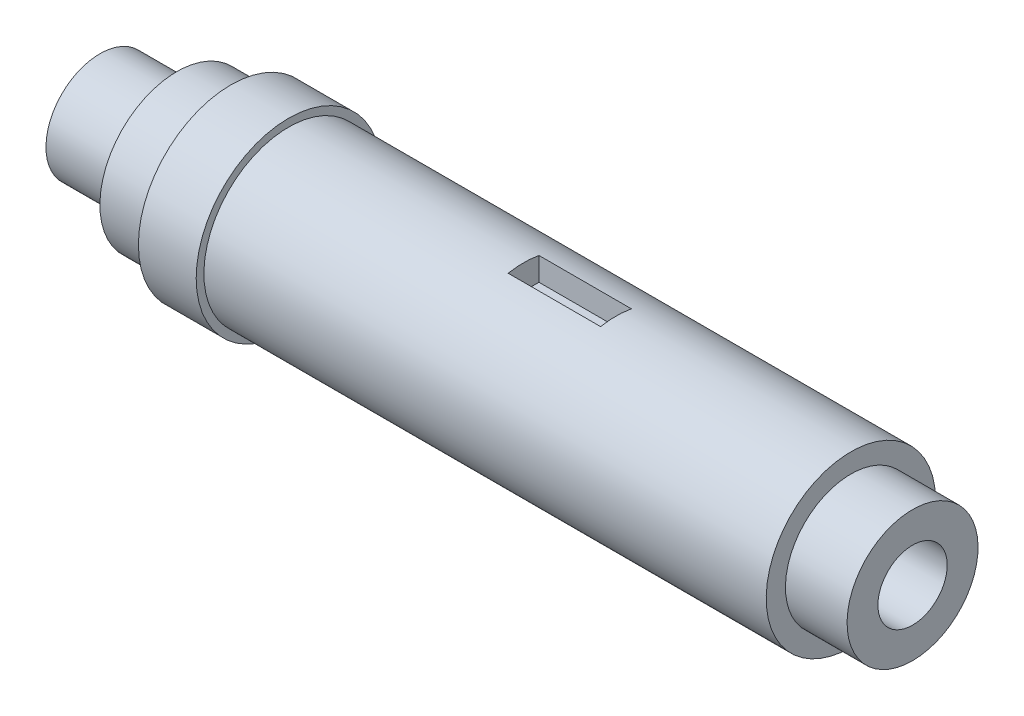
SolidWorks part; units mm, degrees
ref_plane "Front Plane" through (0, 0, 0) normal (0, 0, 1) x (1, 0, 0)
ref_plane "Top Plane" through (0, 0, 0) normal (0, 1, 0) x (1, 0, 0)
ref_plane "Right Plane" through (0, 0, 0) normal (1, 0, 0) x (0, 0, -1)
other "Center of Mass" [suppressed]
sketch "Sketch3" plane through (0, 0, 0) normal (0, 0, 1) x (1, 0, 0)
  line L0 (0, 0) -> (0, 39.0464) construction
  line L1 (-72.5, 0) -> (72.5, 0) construction
  line L2 (-72.5, 2.5) -> (-72.5, 0) construction
  line L3 (-72.5, 2.5) -> (-72.5, 7)
  line L4 (-72.5, 7) -> (-62.5, 7)
  line L5 (-62.5, 7) -> (-62.5, 10)
  line L6 (-62.5, 10) -> (-55.5, 10)
  line L7 (-55.5, 10) -> (-55.5, 12)
  line L8 (-55.5, 12) -> (-38.5, 12)
  line L9 (-38.5, 12) -> (-38.5, 20)
  line L10 (-38.5, 20) -> (-26.5, 20)
  line L11 (-26.5, 20) -> (-26.5, 11)
  line L12 (-26.5, 11) -> (3.5, 11)
  line L13 (3.5, 11) -> (3.5, 10)
  line L14 (3.5, 10) -> (35.5, 10)
  line L15 (35.5, 10) -> (35.5, 8.5)
  line L17 (72.5, 7.5) -> (72.5, 2.5)
  line L18 (72.5, 2.5) -> (-72.5, 2.5)
  line L19 (-32.5, 20) -> (-32.5, 2.5) construction
  line L20 (-11.5, 11) -> (-11.5, 2.5) construction
  line L21 (-77.5, 12) -> (-72.8417, 12) construction
  line L22 (-62.5, 10) -> (-62.5, 16) construction
  line L23 (-77.5, 15) -> (-72.8417, 15) construction
  line L24 (35.5, 8.5) -> (42.5, 8.5)
  line L25 (11.9511, 11) -> (20.8732, 11) construction
  line L26 (30.861, 12) -> (33.3773, 12) construction
  line L27 (42.5, 8.5) -> (42.5, 7.5)
  line L36 (42.5, 7.5) -> (72.5, 7.5)
  line L38 (35.5, 8.5) -> (44.5, 8.5) construction
  point P5 (0, 0)
  dimension "D3" = 40
  dimension "D2" = 22
  dimension "D4" = 40
  dimension "D5" = 12
  dimension "D6" = 10
  dimension "D7" = 7
  dimension "D9" = 5
  dimension "D10" = 14
  dimension "D11" = 20
  dimension "D12" = 12
  dimension "D13" = 24
  dimension "D14" = 32
  dimension "D15" = 15
  dimension "D16" = 20
  dimension "D18" = 11
  dimension "D20" = 12
  dimension "D21" = 7
  dimension "D22" = 17
  dimension "D24" = 15
  dimension "D8" = 30
  dimension "D17" = 32
  dimension "D19" = 30
revolve "Revolve1" [suppressed] add sketch "Sketch3" angle 360 about L1
ref_plane "Plane1" [suppressed] through (0, 11, 0) normal (0, 1, 0) x (1, 0, 0)
sketch "Sketch4" [suppressed] plane through (0, 11, 0) normal (0, 1, 0) x (1, 0, 0)
  line L0 (3.5, 0) -> (-26.5, 0) construction
  line L1 (3.5, -11) -> (3.5, 11) construction
  line L2 (-26.5, -11) -> (-26.5, 11) construction
  line L3 (-11.5, 0) -> (-11.5, 23.5234) construction
  line L4 (72.5, -7.5) -> (72.5, 7.5) construction
  line L5 (72.5, 0) -> (62.5, 0) construction
  line L6 (-17.5, -2) -> (-5.5, -2)
  line L7 (-17.5, -2) -> (-17.5, 2)
  line L8 (-17.5, 2) -> (-5.5, 2)
  line L9 (-5.5, -2) -> (-5.5, 2)
  line L10 (-17.5, -2) -> (-5.5, 2) construction
  line L11 (-17.5, 2) -> (-5.5, -2) construction
  line L16 (56.5, -2) -> (68.5, -2)
  line L17 (56.5, -2) -> (56.5, 2)
  line L18 (56.5, 2) -> (68.5, 2)
  line L19 (68.5, -2) -> (68.5, 2)
  line L20 (56.5, -2) -> (68.5, 2) construction
  line L21 (56.5, 2) -> (68.5, -2) construction
  point P17 (62.5, 0)
  dimension "D1" = 12
  dimension "D2" = 4
  dimension "D3" = 10
  dimension "D4" = 12
  dimension "D5" = 4
extrude "Cut-Extrude1" [suppressed] cut sketch "Sketch4" against normal blind 3.2 contours L6 L9 L8 L7
fillet "Fillet1" [suppressed] radius 1
ref_plane "Plane2" [suppressed] through (0, 7.5, 0) normal (0, 1, 0) x (1, 0, 0)
sketch "Sketch5" [suppressed] plane through (0, 7.5, 0) normal (0, 1, 0) x (1, 0, 0)
  line L0 (68.5, -2) -> (68.5, 2) construction
  line L1 (56.5, -2) -> (68.5, -2) construction
  line L2 (56.5, -2) -> (56.5, 2) construction
  line L3 (56.5, 2) -> (68.5, 2) construction
  line L4 (68.5, -2) -> (68.5, 2)
  line L5 (56.5, -2) -> (68.5, -2)
  line L6 (56.5, -2) -> (56.5, 2)
  line L7 (56.5, 2) -> (68.5, 2)
extrude "Cut-Extrude3" [suppressed] cut sketch "Sketch5" against normal blind 3.2 contours L5 L4 L7 L6
sketch "Sketch6" plane through (0, 0, 0) normal (0, 0, 1) x (1, 0, 0)
  line L0 (-52.75, 0) -> (52.75, 0) construction
  line L1 (-52.75, 4.5) -> (-52.75, 7)
  line L2 (-52.75, 7) -> (-42.75, 7)
  line L3 (-42.75, 7) -> (-42.75, 10)
  line L4 (-42.75, 10) -> (-35.75, 10)
  line L5 (-35.75, 10) -> (-35.75, 12)
  line L6 (-35.75, 12) -> (-28.25, 12)
  line L7 (-28.25, 12) -> (-28.25, 11)
  line L8 (-28.25, 11) -> (44.75, 11)
  line L9 (44.75, 11) -> (44.75, 8.5)
  line L10 (44.75, 8.5) -> (52.75, 8.5)
  line L11 (52.75, 8.5) -> (52.75, 4.5)
  line L12 (52.75, 4.5) -> (-52.75, 4.5)
  line L13 (8.25, 11) -> (8.25, 4.5) construction
  point P4 (0, 0)
  point P17 (0, 0)
  dimension "D1" = 10
  dimension "D2" = 7
  dimension "D3" = 8
  dimension "D4" = 61
  dimension "D5" = 105.5
  dimension "D6" = 7
  dimension "D7" = 10
  dimension "D8" = 12
  dimension "D9" = 11
  dimension "D10" = 8.5
  dimension "D11" = 9
revolve "Revolve2" add sketch "Sketch6" angle 360 about L0
ref_plane "Plane3" through (0, 11, 0) normal (0, 1, 0) x (1, 0, 0)
sketch "Sketch7" plane through (0, 11, 0) normal (0, 1, 0) x (1, 0, 0)
  line L0 (-28.25, 0) -> (44.75, 0) construction
  line L1 (-28.25, -12) -> (-28.25, 12) construction
  line L2 (44.75, -8.5) -> (44.75, 8.5) construction
  line L4 (2.25, -2) -> (14.25, -2)
  line L5 (2.25, -2) -> (2.25, 2)
  line L6 (2.25, 2) -> (14.25, 2)
  line L7 (14.25, -2) -> (14.25, 2)
  line L8 (2.25, -2) -> (14.25, 2) construction
  line L9 (2.25, 2) -> (14.25, -2) construction
  point P6 (8.25, 0)
  dimension "D1" = 4
  dimension "D2" = 12
extrude "Cut-Extrude4" cut sketch "Sketch7" against normal blind 3.2
equation "\"mainShaft-D\"= 20mm"
equation "\"mainTrackGear-D\"= 40mm"
equation "\"D4@Sketch3\"=\"mainTrackGear-D\""
equation "\"D11@Sketch3\"=\"mainShaft-D\""
